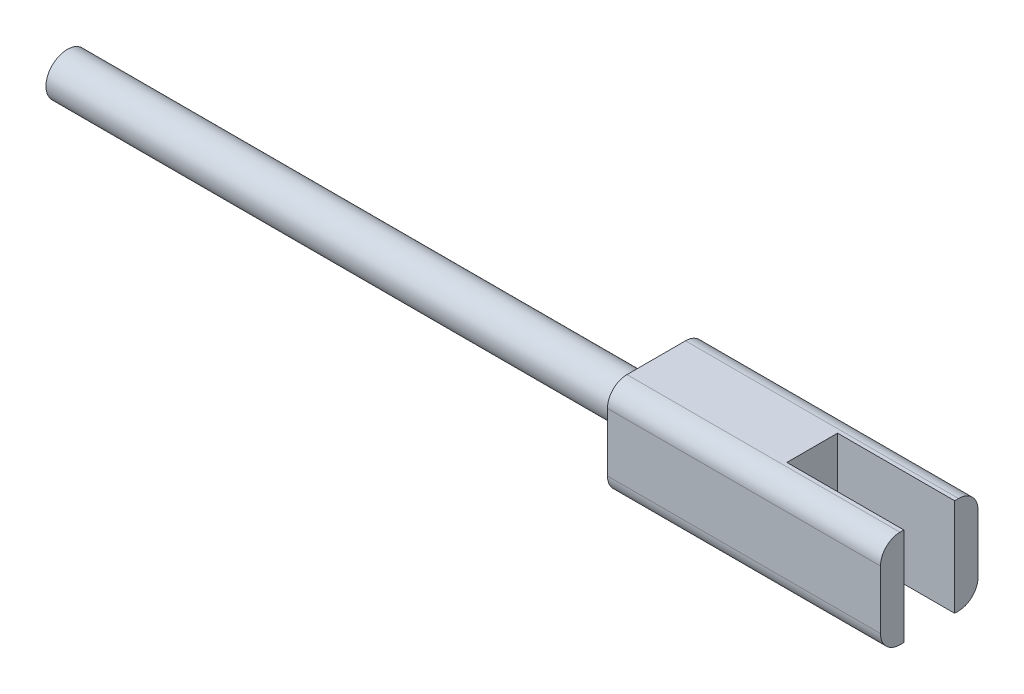
SolidWorks part; units mm, degrees
ref_plane "Front Plane" through (0, 0, 0) normal (0, 0, 1) x (1, 0, 0)
ref_plane "Top Plane" through (0, 0, 0) normal (0, 1, 0) x (1, 0, 0)
ref_plane "Right Plane" through (0, 0, 0) normal (1, 0, 0) x (0, 0, -1)
sketch "Sketch1" plane through (0, 0, 0) normal (1, 0, 0) x (0, 0, -1)
  circle A0 centre (0, 0) radius 1.09
extrude "Boss-Extrude1" add sketch "Sketch1" along normal blind 32.2
ref_plane "Plane1" through (30.2, 0, 0) normal (1, 0, 0) x (0, 0, -1)
sketch "Sketch2" plane through (30.2, 0, 0) normal (1, 0, 0) x (0, 0, -1)
  line L0 (-1.5, -2.5) -> (1.5, -2.5)
  line L1 (2.5, -1.5) -> (2.5, 1.5)
  line L2 (1.5, 2.5) -> (-1.5, 2.5)
  line L3 (-2.5, 1.5) -> (-2.5, -1.5)
  arc A0 (1.5, -2.5) -> (2.5, -1.5) centre (1.5, -1.5) ccw
  arc A1 (2.5, 1.5) -> (1.5, 2.5) centre (1.5, 1.5) ccw
  arc A2 (-1.5, 2.5) -> (-2.5, 1.5) centre (-1.5, 1.5) ccw
  arc A3 (-2.5, -1.5) -> (-1.5, -2.5) centre (-1.5, -1.5) ccw
extrude "Boss-Extrude2" add sketch "Sketch2" along normal blind 14
sketch "Sketch3" plane through (0, 0, 0) normal (0, 1, 0) x (1, 0, 0)
  line L0 (38.2, 1.3) -> (45.2, 1.3)
  line L1 (45.2, 1.3) -> (45.2, -1.3)
  line L2 (45.2, -1.3) -> (38.2, -1.3)
  line L3 (38.2, -1.3) -> (38.2, 1.3)
extrude "Cut-Extrude1" cut sketch "Sketch3" against normal through all and the other way through all
